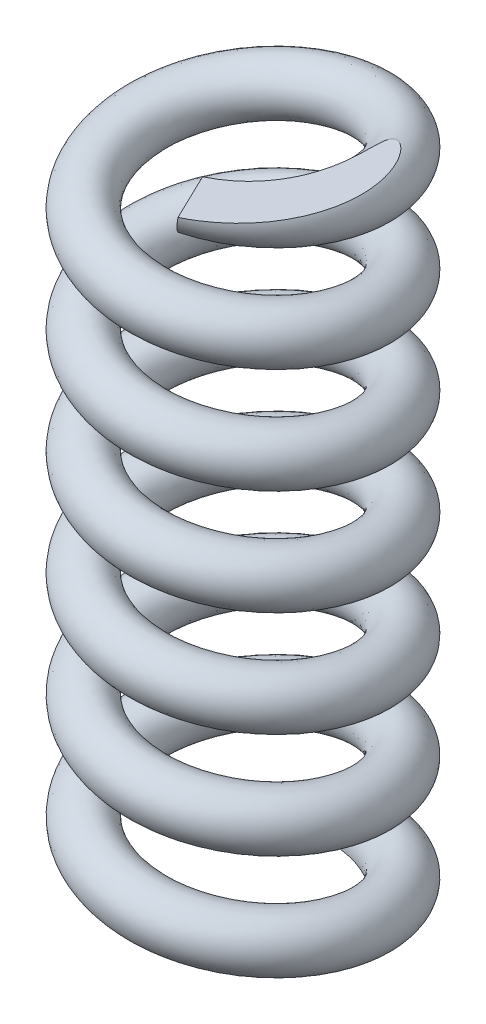
SolidWorks part; units mm, degrees
ref_plane "Спереди" through (0, 0, 0) normal (0, 0, 1) x (1, 0, 0)
ref_plane "Сверху" through (0, 0, 0) normal (0, 1, 0) x (1, 0, 0)
ref_plane "Справа" through (0, 0, 0) normal (1, 0, 0) x (0, 0, -1)
sketch "Эскиз1" plane through (0, 0, 0) normal (0, 1, 0) x (1, 0, 0)
  circle A0 centre (0, 0) radius 7.5
  dimension "D1" = 15
curve "Спираль1" pitch 7 height 45 turns 6.4286
sweep "По траектории5" add path "Спираль1" circular profile diameter 3.5 parameters "D3"=3.5
sketch "Эскиз89" plane through (0, 0, 0) normal (0, 0, 1) x (1, 0, 0)
  line L1 (18.161, 0) -> (-28.8383, 0)
  line L2 (18.161, 0) -> (18.161, 45)
  line L3 (18.161, 45) -> (-28.8383, 45)
  line L4 (-28.8383, 0) -> (-28.8383, 45)
  line L5 (32.1682, -7.2464) -> (-37.8099, -7.2464)
  line L6 (32.1682, -7.2464) -> (32.1682, 55.0288)
  line L7 (32.1682, 55.0288) -> (-37.8099, 55.0288)
  line L8 (-37.8099, -7.2464) -> (-37.8099, 55.0288)
  dimension "D1" = 45
extrude "Вырез-Вытянуть2" cut sketch "Эскиз89" against normal through all both and the other way through all contours L8 L5 L6 L7 L1 L4 L3 L2
